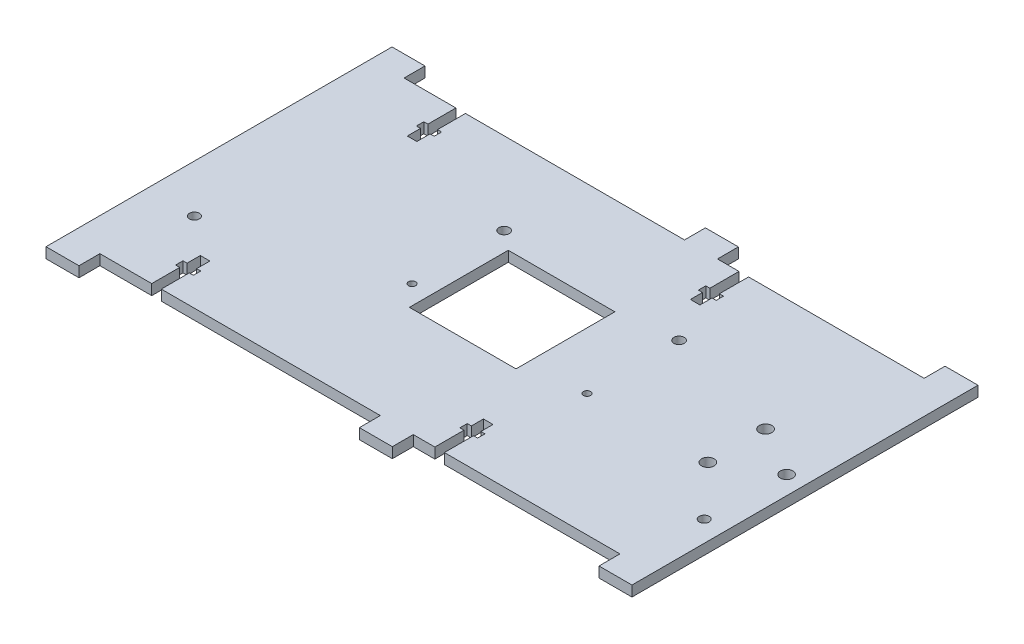
SolidWorks part; units mm, degrees
ref_plane "Front Plane" through (0, 0, 0) normal (0, 0, 1) x (1, 0, 0)
ref_plane "Top Plane" through (0, 0, 0) normal (0, 1, 0) x (1, 0, 0)
ref_plane "Right Plane" through (0, 0, 0) normal (1, 0, 0) x (0, 0, -1)
sketch "Sketch1" plane through (0, 0, 0) normal (0, 1, 0) x (1, 0, 0)
  line L0 (-67.1586, 70.4843) -> (-67.1586, 74.4928)
  line L1 (-92.8881, 91.5843) -> (-82.8881, 91.5843)
  line L2 (-92.8881, 91.5843) -> (-92.8881, -13.4157)
  line L3 (84.9141, 91.5843) -> (84.9141, -13.4157)
  line L5 (-64.2586, 85.2343) -> (2.2019, 85.2343)
  line L6 (-67.1586, 85.2343) -> (-67.1586, 76.7428)
  line L7 (-67.1586, 70.4843) -> (-64.2586, 70.4843)
  line L8 (-64.2586, 85.2343) -> (-64.2586, 76.7428)
  line L9 (-68.4086, 76.7428) -> (-67.1586, 76.7428)
  line L10 (-68.4086, 76.7428) -> (-68.4086, 74.4928)
  line L11 (-68.4086, 74.4928) -> (-67.1586, 74.4928)
  line L12 (-63.0086, 76.7428) -> (-63.0086, 74.4928)
  line L13 (18.7441, 70.4843) -> (18.7441, 74.1476)
  line L14 (-82.8881, 91.5843) -> (-82.8881, 85.2343)
  line L15 (-82.8881, 85.2343) -> (-67.1586, 85.2343)
  line L16 (2.2019, 91.5843) -> (2.2019, 85.2343)
  line L17 (-64.2586, 70.4843) -> (-64.2586, 74.4928)
  line L18 (-64.2586, 74.4928) -> (-63.0086, 74.4928)
  line L19 (-64.2586, 76.7428) -> (-63.0086, 76.7428)
  line L20 (2.2019, 91.5843) -> (12.2019, 91.5843)
  line L21 (21.6441, 85.2343) -> (74.9141, 85.2343)
  line L22 (18.7441, 85.2343) -> (18.7441, 76.3976)
  line L23 (18.7441, 70.4843) -> (21.6441, 70.4843)
  line L24 (21.6441, 85.2343) -> (21.6441, 76.3976)
  line L25 (17.4941, 76.3976) -> (18.7441, 76.3976)
  line L26 (17.4941, 76.3976) -> (17.4941, 74.1476)
  line L27 (17.4941, 74.1476) -> (18.7441, 74.1476)
  line L28 (22.8941, 76.3976) -> (22.8941, 74.1476)
  line L29 (12.2019, 91.5843) -> (12.2019, 85.2343)
  line L30 (12.2019, 85.2343) -> (18.7441, 85.2343)
  line L31 (74.9141, 91.5843) -> (74.9141, 85.2343)
  line L32 (21.6441, 70.4843) -> (21.6441, 74.1476)
  line L33 (21.6441, 74.1476) -> (22.8941, 74.1476)
  line L34 (21.6441, 76.3976) -> (22.8941, 76.3976)
  line L35 (74.9141, 91.5843) -> (84.9141, 91.5843)
  line L36 (-82.8881, -7.0657) -> (-67.1586, -7.0657)
  line L37 (74.9141, -13.4157) -> (84.9141, -13.4157)
  line L38 (21.6441, 1.771) -> (22.8941, 1.771)
  line L39 (21.6441, 4.021) -> (22.8941, 4.021)
  line L40 (21.6441, 7.6843) -> (21.6441, 4.021)
  line L41 (74.9141, -13.4157) -> (74.9141, -7.0657)
  line L42 (12.2019, -7.0657) -> (18.7441, -7.0657)
  line L43 (12.2019, -13.4157) -> (12.2019, -7.0657)
  line L44 (22.8941, 1.771) -> (22.8941, 4.021)
  line L45 (17.4941, 4.021) -> (18.7441, 4.021)
  line L46 (17.4941, 1.771) -> (17.4941, 4.021)
  line L47 (17.4941, 1.771) -> (18.7441, 1.771)
  line L48 (21.6441, -7.0657) -> (21.6441, 1.771)
  line L49 (18.7441, 7.6843) -> (21.6441, 7.6843)
  line L50 (18.7441, -7.0657) -> (18.7441, 1.771)
  line L51 (21.6441, -7.0657) -> (74.9141, -7.0657)
  line L52 (2.2019, -13.4157) -> (12.2019, -13.4157)
  line L53 (-64.2586, 1.4258) -> (-63.0086, 1.4258)
  line L54 (-64.2586, 3.6758) -> (-63.0086, 3.6758)
  line L55 (-64.2586, 7.6843) -> (-64.2586, 3.6758)
  line L56 (2.2019, -13.4157) -> (2.2019, -7.0657)
  line L57 (-82.8881, -13.4157) -> (-82.8881, -7.0657)
  line L58 (18.7441, 7.6843) -> (18.7441, 4.021)
  line L59 (-63.0086, 1.4258) -> (-63.0086, 3.6758)
  line L60 (-68.4086, 3.6758) -> (-67.1586, 3.6758)
  line L61 (-68.4086, 1.4258) -> (-68.4086, 3.6758)
  line L62 (-68.4086, 1.4258) -> (-67.1586, 1.4258)
  line L63 (-64.2586, -7.0657) -> (-64.2586, 1.4258)
  line L64 (-67.1586, 7.6843) -> (-64.2586, 7.6843)
  line L65 (-67.1586, -7.0657) -> (-67.1586, 1.4258)
  line L66 (-64.2586, -7.0657) -> (2.2019, -7.0657)
  line L67 (-92.8881, -13.4157) -> (-82.8881, -13.4157)
  line L68 (-67.1586, 7.6843) -> (-67.1586, 3.6758)
  line L69 (-21.8187, 55.7843) -> (10.5266, 55.7843)
  line L70 (-21.8187, 55.7843) -> (-21.8187, 25.7843)
  line L71 (-21.8187, 25.7843) -> (10.5266, 25.7843)
  line L72 (10.5266, 55.7843) -> (10.5266, 25.7843)
  circle A1 centre (79.3541, 39.0843) radius 1.9
  circle A2 centre (64.1987, 30.3343) radius 1.9
  circle A3 centre (64.1987, 47.8343) radius 1.9
  circle A4 centre (27.7774, 58.0256) radius 1.5835
  circle A5 centre (78.5774, 14.8456) radius 1.5071
  circle A6 centre (27.7774, 30.0856) radius 1.0795
  circle A7 centre (-78.423, 17.1475) radius 1.5071
  circle A8 centre (-27.6231, 32.3875) radius 1.0795
  circle A9 centre (-27.6231, 60.3275) radius 1.5835
  point P72 (84.9141, 39.0843)
  point P76 (-21.8187, 40.7843)
  dimension "D1" = 1.25
  dimension "D2" = 2.9
  dimension "D3" = 1.25
  dimension "D4" = 2.25
  dimension "D5" = 14.75
  dimension "D6" = 1.25
  dimension "D7" = 1.25
  dimension "D8" = 2.25
  dimension "D9" = 14.75
  dimension "D10" = 10
  dimension "D11" = 10
  dimension "D12" = 10
  dimension "D13" = 6.35
  dimension "D14" = 6.35
  dimension "D15" = 53.27
  dimension "D16" = 105
  dimension "D17" = 95.09
  dimension "D18" = 30
  dimension "D19" = 105
  dimension "D20" = 5.56
  dimension "D21" = 17.5
  dimension "D22" = 17.5
  dimension "D23" = 50.8
  dimension "D24" = 6.35
extrude "Extrude1" add sketch "Sketch1" along normal blind 3.175
